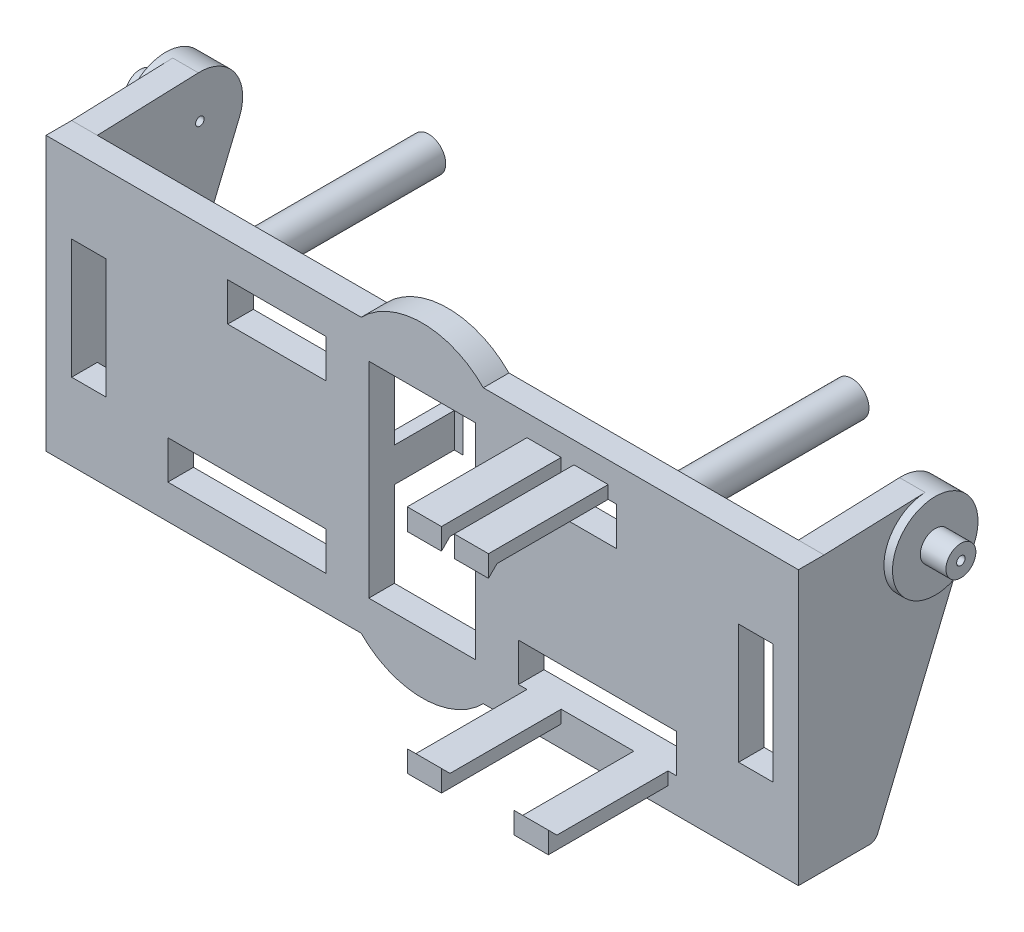
SolidWorks part; units mm, degrees
ref_plane "Plan de face" through (0, 0, 0) normal (0, 0, 1) x (1, 0, 0)
ref_plane "Plan de dessus" through (0, 0, 0) normal (0, 1, 0) x (1, 0, 0)
ref_plane "Plan de droite" through (0, 0, 0) normal (1, 0, 0) x (0, 0, -1)
sketch "Esquisse1" plane through (0, 0, 0) normal (0, 0, 1) x (1, 0, 0)
  line L0 (-44, 32) -> (-44, 28)
  line L1 (0, 0) -> (-44, 0)
  line L2 (0, 0) -> (0, 32)
  line L3 (0, 32) -> (-44, 32)
  line L4 (-44, 28) -> (-37.75, 28)
  line L5 (-37.75, 28) -> (-37.75, 4)
  line L6 (-37.75, 4) -> (-44, 4)
  line L7 (-44, 4) -> (-44, 0)
  line L9 (-32.75, 28) -> (-21.25, 28)
  line L10 (-32.75, 28) -> (-32.75, 23.5)
  line L11 (-32.75, 23.5) -> (-21.25, 23.5)
  line L12 (-21.25, 28) -> (-21.25, 23.5)
  line L17 (-32.75, 8.5) -> (-14.25, 8.5)
  line L18 (-32.75, 8.5) -> (-32.75, 4)
  line L19 (-32.75, 4) -> (-14.25, 4)
  line L20 (-14.25, 8.5) -> (-14.25, 4)
  line L25 (-7, 23) -> (-3, 23)
  line L26 (-7, 23) -> (-7, 9)
  line L27 (-7, 9) -> (-3, 9)
  line L28 (-3, 23) -> (-3, 9)
  dimension "D1" = 32
  dimension "D2" = 44
  dimension "D3" = 37.75
  dimension "D4" = 24
  dimension "D5" = 4
  dimension "D6" = 11.5
  dimension "D7" = 4.5
  dimension "D8" = 4
  dimension "D9" = 5
  dimension "D10" = 5
  dimension "D11" = 4.5
  dimension "D12" = 18.5
  dimension "D13" = 3
  dimension "D14" = 4
  dimension "D15" = 14
  dimension "D16" = 9
  dimension "D17" = 4
  dimension "D18" = 44
extrude "Boss.-Extru.1" add sketch "Esquisse1" along normal blind 3
sketch "Esquisse2" plane through (0, 0, 0) normal (1, 0, 0) x (0, 0, -1)
  line L0 (0, 32) -> (11.8224, 32.4202)
  line L1 (16.616, 25.5017) -> (6.2563, 0.6157)
  line L2 (5.3331, 0) -> (0, 0)
  line L3 (0, 32) -> (0, 0)
  arc A0 (16.616, 25.5017) -> (11.8224, 32.4202) centre (12, 27.4233) ccw
  arc A1 (5.3331, 0) -> (6.2563, 0.6157) centre (5.3331, 1) ccw
  point P8 (19.6113, 32.697)
  point P11 (6, 0)
  dimension "D3" = 5
  dimension "D4" = 1
  dimension "D1" = 12
  dimension "D2" = 6
extrude "Boss.-Extru.2" add sketch "Esquisse2" against normal blind 3
sketch "Esquisse3" plane through (0, 0, 0) normal (0, 0, -1) x (-1, 0, 0)
  line L0 (3, 32) -> (44, 32) construction
  line L1 (21.25, 23.5) -> (21.25, 28) construction
  circle A0 centre (19.25, 27) radius 2
  circle A1 centre (19.25, 27) radius 0.5
  dimension "D1" = 4
  dimension "D2" = 1
  dimension "D3" = 5
extrude "Boss.-Extru.3" add sketch "Esquisse3" along normal blind 22.5
sketch "Esquisse4" plane through (0, 0, 0) normal (1, 0, 0) x (0, 0, -1)
  circle A0 centre (12, 27.4233) radius 5
  arc A1 (16.616, 25.5017) -> (11.8224, 32.4202) centre (12, 27.4233) ccw construction
  dimension "D1" = 10
extrude "Boss.-Extru.4" add sketch "Esquisse4" along normal blind 1
sketch "Esquisse5" plane through (1, 0, 0) normal (1, 0, 0) x (0, 0, -1)
  circle A0 centre (12, 27.4233) radius 1.75
  circle A1 centre (12, 27.4233) radius 5 construction
  dimension "D1" = 3.5
extrude "Boss.-Extru.5" add sketch "Esquisse5" along normal blind 3
sketch "Esquisse6" plane through (4, 0, 0) normal (1, 0, 0) x (0, 0, -1)
  circle A0 centre (12, 27.4233) radius 0.5
  dimension "D1" = 1
extrude "Enlèv. mat.-Extru.1" cut sketch "Esquisse6" against normal up to surface (7 mm away) up to face at (-3, 16.4918, -3.6256)
sketch "Esquisse8" plane through (0, 0, 0) normal (0, 0, -1) x (-1, 0, 0)
  line L0 (37.75, 28) -> (37.75, 4) construction
  line L1 (37.75, 18) -> (36.25, 18)
  line L2 (37.75, 18) -> (37.75, 14)
  line L3 (37.75, 14) -> (36.25, 14)
  line L4 (36.25, 18) -> (36.25, 14)
  line L5 (44, 0) -> (3, 0) construction
  dimension "D1" = 4
  dimension "D2" = 1.5
  dimension "D3" = 14
extrude "Boss.-Extru.7" add sketch "Esquisse8" along normal blind 8
sketch "Esquisse9" plane through (0, 14, 0) normal (0, -1, 0) x (1, 0, 0)
  line L0 (-37.75, -8) -> (-38.75, -7)
  line L1 (-38.75, -7) -> (-37.75, -7)
  line L2 (-37.75, -8) -> (-37.75, 0) construction
  line L3 (-37.75, -7) -> (-37.75, -8)
  dimension "D1" = 1
  dimension "D2" = 1
extrude "Boss.-Extru.8" add sketch "Esquisse9" against normal up to surface (4 mm away) up to face at (-37, 18, -4)
mirror "Symétrie1" about plane through (-44, 32, 3) normal (1, 0, 0) of "Boss.-Extru.8", "Boss.-Extru.7", "Boss.-Extru.4", "Boss.-Extru.2", "Boss.-Extru.1", "Boss.-Extru.3", "Boss.-Extru.5", "Enlèv. mat.-Extru.1"
sketch "Esquisse7" plane through (0, 0, 0) normal (0, 0, -1) x (-1, 0, 0)
  line L0 (3, 32) -> (85, 32) construction
  line L1 (35.3911, 30.088) -> (52.6089, 30.088)
  line L2 (37.75, 28) -> (37.75, 18) construction
  arc A0 (52.6089, 30.088) -> (35.3911, 30.088) centre (44, 25) ccw
  dimension "D1" = 20
  dimension "D3" = 6.25
  dimension "D2" = 7
extrude "Boss.-Extru.6" add sketch "Esquisse7" against normal up to surface (3 mm away) up to face at (-44, 16, 3)
ref_plane "Plan1" through (0, 16, 0) normal (0, -1, 0) x (1, 0, 0)
mirror "Symétrie2" about plane through (0, 16, 0) normal (0, -1, 0) of "Boss.-Extru.6"
sketch "Esquisse10" plane through (0, 0, 3) normal (0, 0, 1) x (1, 0, 0)
  line L0 (-21.25, 28) -> (-32.75, 28) construction
  line L1 (-31.75, 28) -> (-27.75, 28)
  line L2 (-31.75, 28) -> (-31.75, 29.5)
  line L3 (-31.75, 29.5) -> (-27.75, 29.5)
  line L4 (-27.75, 28) -> (-27.75, 29.5)
  line L5 (-32.75, 4) -> (-14.25, 4) construction
  line L6 (-26.25, 28) -> (-22.25, 28)
  line L7 (-26.25, 28) -> (-26.25, 29.5)
  line L8 (-26.25, 29.5) -> (-22.25, 29.5)
  line L9 (-22.25, 28) -> (-22.25, 29.5)
  line L10 (-31.75, 4) -> (-27.75, 4)
  line L11 (-31.75, 4) -> (-31.75, 2.5)
  line L12 (-31.75, 2.5) -> (-27.75, 2.5)
  line L13 (-27.75, 4) -> (-27.75, 2.5)
  line L14 (-32.75, 28) -> (-32.75, 23.5) construction
  line L15 (-15.25, 4) -> (-19.25, 4)
  line L16 (-15.25, 4) -> (-15.25, 2.5)
  line L17 (-15.25, 2.5) -> (-19.25, 2.5)
  line L18 (-19.25, 4) -> (-19.25, 2.5)
  line L19 (-21.25, 23.5) -> (-21.25, 28) construction
  line L20 (-14.25, 4) -> (-14.25, 8.5) construction
  line L21 (-32.75, 8.5) -> (-32.75, 4) construction
  dimension "D1" = 1.5
  dimension "D2" = 1.5
  dimension "D3" = 1.5
  dimension "D4" = 1.5
  dimension "D5" = 4
  dimension "D6" = 4
  dimension "D7" = 4
  dimension "D8" = 4
  dimension "D9" = 1
  dimension "D10" = 1
  dimension "D11" = 1
  dimension "D12" = 1
extrude "Boss.-Extru.9" add sketch "Esquisse10" along normal blind 14
sketch "Esquisse11" plane through (-15.25, 0, 0) normal (1, 0, 0) x (0, 0, -1)
  line L0 (-17, 4) -> (-17, 5)
  line L1 (-17, 5) -> (-16, 4)
  line L2 (-17, 4) -> (-3, 4) construction
  line L3 (-16, 4) -> (-17, 4)
  dimension "D1" = 1
  dimension "D2" = 1
extrude "Boss.-Extru.11" add sketch "Esquisse11" against normal up to surface (4 mm away) up to face at (-19.25, 3.25, 10)
sketch "Esquisse12" plane through (-27.75, 0, 0) normal (1, 0, 0) x (0, 0, -1)
  line L0 (-17, 4) -> (-17, 5)
  line L1 (-17, 5) -> (-16, 4)
  line L2 (-17, 4) -> (-3, 4) construction
  line L3 (-16, 4) -> (-17, 4)
  dimension "D1" = 1
  dimension "D2" = 1
extrude "Boss.-Extru.12" add sketch "Esquisse12" against normal up to surface (4 mm away) up to face at (-31.75, 3.25, 10)
sketch "Esquisse13" plane through (-22.25, 0, 0) normal (1, 0, 0) x (0, 0, -1)
  line L0 (-17, 28) -> (-17, 27)
  line L1 (-17, 27) -> (-16, 28)
  line L2 (-17, 28) -> (-3, 28) construction
  line L3 (-16, 28) -> (-17, 28)
  dimension "D1" = 1
  dimension "D2" = 1
extrude "Boss.-Extru.13" add sketch "Esquisse13" against normal up to surface (4 mm away) up to face at (-26.25, 28.75, 10)
sketch "Esquisse14" plane through (-31.75, 0, 0) normal (-1, 0, 0) x (0, 0, 1)
  line L0 (17, 28) -> (16, 28)
  line L1 (17, 28) -> (3, 28) construction
  line L2 (16, 28) -> (17, 27)
  line L3 (17, 27) -> (17, 28)
  dimension "D1" = 1
  dimension "D2" = 1
extrude "Boss.-Extru.14" add sketch "Esquisse14" against normal up to surface (4 mm away) up to face at (-27.75, 28.75, 10)
